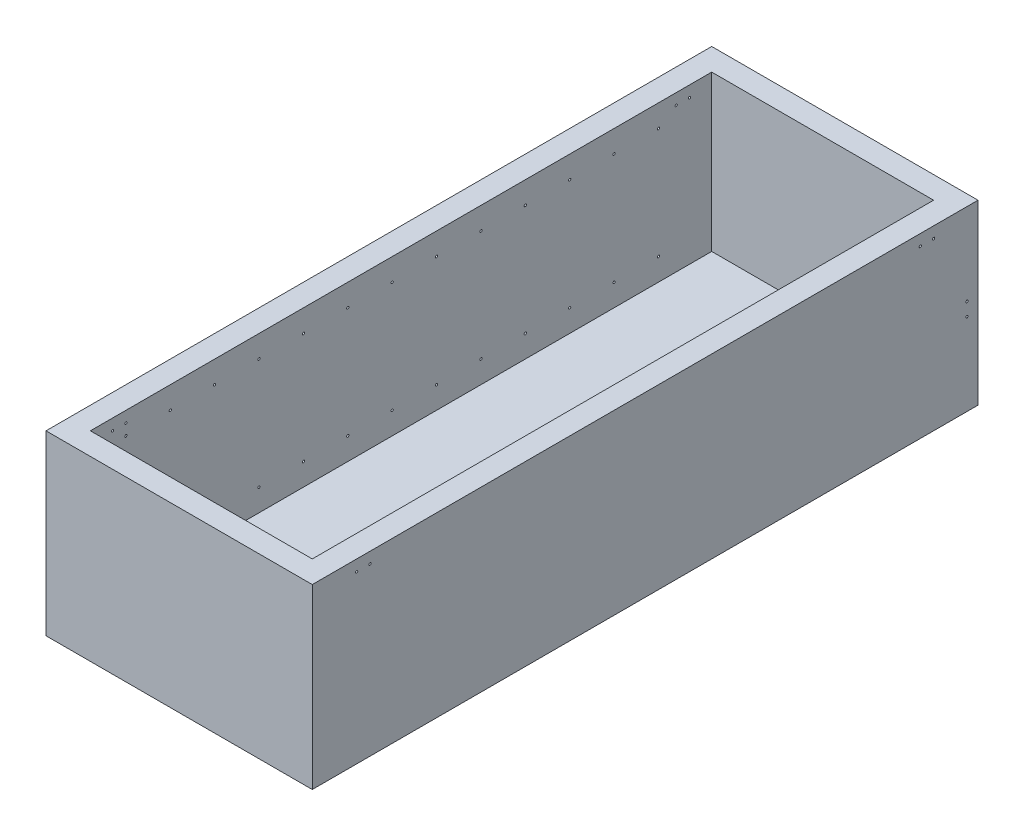
SolidWorks part; units mm, degrees
ref_plane "Front Plane" through (0, 0, 0) normal (0, 0, 1) x (1, 0, 0)
ref_plane "Top Plane" through (0, 0, 0) normal (0, 1, 0) x (1, 0, 0)
ref_plane "Right Plane" through (0, 0, 0) normal (1, 0, 0) x (0, 0, -1)
sketch "Sketch1" plane through (0, 0, 0) normal (0, 1, 0) x (1, 0, 0)
  line L1 (-300, 750) -> (300, 750)
  line L2 (-300, 750) -> (-300, -750)
  line L3 (-300, -750) -> (300, -750)
  line L4 (300, 750) -> (300, -750)
  dimension "D1" = 600
  dimension "D2" = 1500
  dimension "D3" = 300
  dimension "D4" = 750
extrude "Boss-Extrude1" add sketch "Sketch1" along normal blind 400
shell "Shell1" thickness 50
sketch "Sketch2" plane through (300, 0, 0) normal (1, 0, 0) x (0, 0, -1)
  line L0 (-750, 400) -> (750, 400) construction
  line L1 (-750, 400) -> (-750, 0) construction
  line L2 (750, 400) -> (750, 0) construction
  circle A0 centre (-650, 375) radius 2.5
  circle A1 centre (-620, 375) radius 2.5
  circle A2 centre (650, 375) radius 2.5
  circle A3 centre (620, 375) radius 2.5
  dimension "D1" = 5
  dimension "D2" = 5
  dimension "D7" = 5
  dimension "D8" = 5
  dimension "D3" = 25
  dimension "D4" = 25
  dimension "D5" = 100
  dimension "D6" = 130
  dimension "D9" = 25
  dimension "D10" = 25
  dimension "D11" = 100
  dimension "D12" = 130
sketch "Sketch12" plane through (300, 0, 0) normal (1, 0, 0) x (0, 0, -1)
extrude "Cut-Extrude1" cut sketch "Sketch2" against normal through all
sketch "Sketch13" plane through (0, 0, 0) normal (1, 0, 0) x (0, 0, -1)
  line L0 (-750, 400) -> (-750, 0) construction
  line L1 (-750, 400) -> (750, 400) construction
  line L2 (-750, 0) -> (750, 0) construction
  circle A0 centre (-620, 350) radius 2.5
  circle A1 centre (-620, 100) radius 2.5
  dimension "D1" = 5
  dimension "D5" = 100
  dimension "D2" = 130
  dimension "D3" = 130
  dimension "D4" = 50
extrude "Cut-Extrude2" cut sketch "Sketch13" against normal mid plane 550
pattern_linear "LPattern1" count 13 spacing 100 along (0, 0, -1) of "Cut-Extrude2"
sketch "Sketch14" plane through (300, 0, 0) normal (1, 0, 0) x (0, 0, -1)
  line L0 (750, 400) -> (750, 0) construction
  line L1 (-750, 0) -> (750, 0) construction
  circle A0 centre (725, 215) radius 2.5
  circle A1 centre (725, 185) radius 2.5
  dimension "D1" = 5
  dimension "D2" = 5
  dimension "D3" = 30
  dimension "D4" = 25
  dimension "D5" = 185
extrude "Cut-Extrude3" cut sketch "Sketch14" against normal blind 25
mirror "Mirror1" about plane through (0, 0, 0) normal (1, 0, 0) of "Cut-Extrude3"
